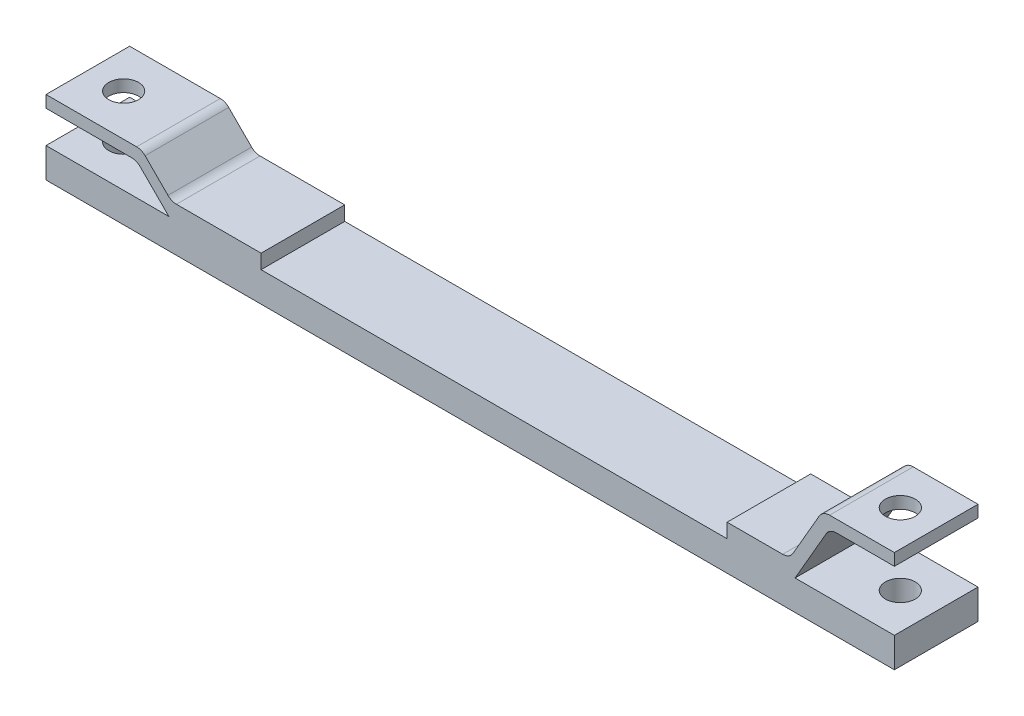
SolidWorks part; units mm, degrees
ref_plane "Front Plane" through (0, 0, 0) normal (0, 0, 1) x (1, 0, 0)
ref_plane "Top Plane" through (0, 0, 0) normal (0, 1, 0) x (1, 0, 0)
ref_plane "Right Plane" through (0, 0, 0) normal (1, 0, 0) x (0, 0, -1)
sketch "Sketch1" plane through (0, 0, 0) normal (0, 0, 1) x (1, 0, 0)
  line L0 (0, 52) -> (75.8579, 52)
  line L1 (0, 0) -> (710, 0)
  line L2 (0, 0) -> (0, 25)
  line L3 (0, 25) -> (710, 25)
  line L4 (710, 0) -> (710, 25)
  line L5 (0, 62) -> (80, 62)
  line L6 (80, 62) -> (105, 37)
  line L7 (105, 37) -> (180, 37)
  line L8 (180, 37) -> (180, 25)
  line L9 (75.8579, 52) -> (100.8579, 27)
  line L10 (710, 85) -> (650, 85)
  line L11 (650, 85) -> (622.2872, 37)
  line L12 (622.2872, 37) -> (570, 37)
  line L13 (570, 37) -> (570, 25)
  line L14 (0, 62) -> (0, 52)
  line L15 (170, 27) -> (170, 25)
  line L16 (710, 75) -> (655.7735, 75)
  line L17 (655.7735, 75) -> (628.0607, 27)
  line L18 (100.8579, 27) -> (102.8579, 25)
  line L19 (710, 85) -> (710, 75)
  line L20 (628.0607, 27) -> (580, 27) construction
  line L21 (580, 27) -> (580, 25) construction
  line L22 (100.8579, 27) -> (170, 27) construction
  line L23 (628.0607, 27) -> (626.906, 25)
  dimension "D1" = 710
  dimension "D2" = 25
  dimension "D3" = 37
  dimension "D4" = 80
  dimension "D5" = 12
  dimension "D6" = 45
  dimension "D7" = 180
  dimension "D8" = 60
  dimension "D9" = 60
  dimension "D10" = 60
  dimension "D11" = 12
  dimension "D12" = 140
  dimension "D13" = 10
  dimension "D14" = 10
extrude "Boss-Extrude1" add sketch "Sketch1" along normal blind 70
fillet "Fillet1" radius 10 6 edges at (75.8579, 52, 35) (655.7735, 75, 35) (622.2872, 37, 35) (650, 85, 35) (105, 37, 35) (80, 62, 35)
sketch "Sketch2" plane through (0, 85, 0) normal (0, 1, 0) x (1, 0, 0)
  line L0 (0, -70) -> (0, 0) construction
  line L1 (710, -70) -> (710, 0) construction
  circle A0 centre (680, -35) radius 12.5
  circle A1 centre (30, -35) radius 12.5
  point P7 (0, -35)
  point P13 (710, -35)
  dimension "D1" = 25
  dimension "D2" = 30
  dimension "D3" = 30
extrude "Cut-Extrude1" cut sketch "Sketch2" against normal through all
